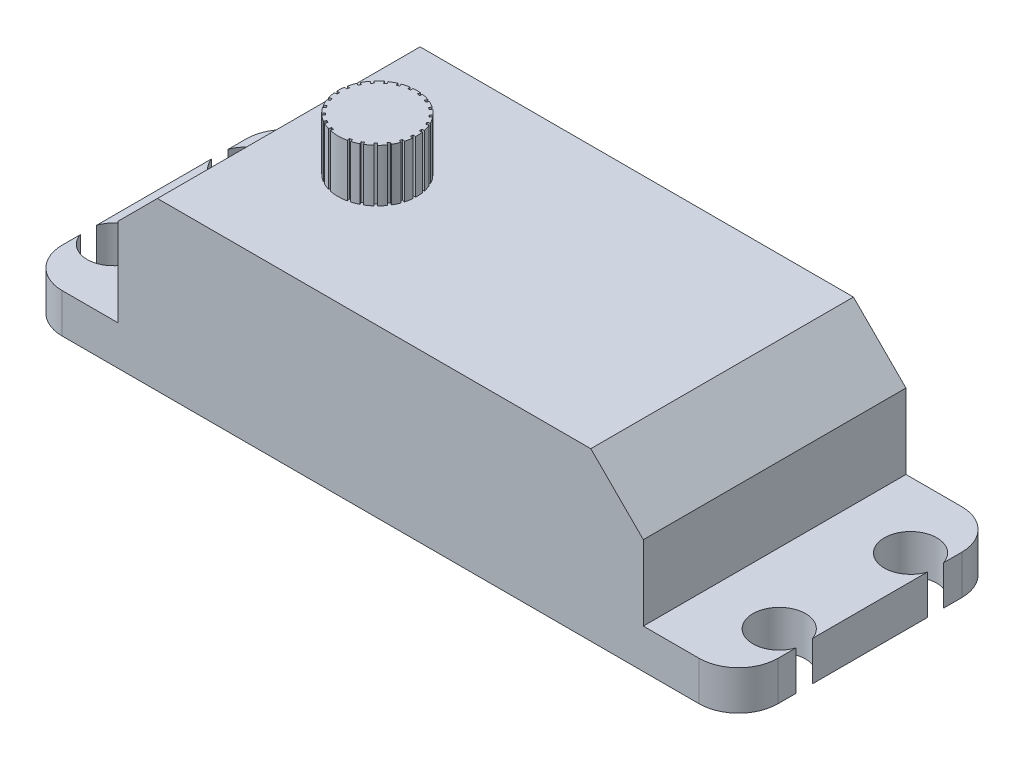
SolidWorks part; units mm, degrees
ref_plane "前视基准面" through (0, 0, 0) normal (0, 0, 1) x (1, 0, 0)
ref_plane "上视基准面" through (0, 0, 0) normal (0, 1, 0) x (1, 0, 0)
ref_plane "右视基准面" through (0, 0, 0) normal (1, 0, 0) x (0, 0, -1)
sketch "草图1" plane through (0, 0, 0) normal (0, 0, 1) x (1, 0, 0)
  line L1 (-20, 6.35) -> (20, 6.35)
  line L2 (-20, 6.35) -> (-20, -6.35)
  line L3 (-20, -6.35) -> (20, -6.35)
  line L4 (20, 6.35) -> (20, -6.35)
  line L5 (-20, 6.35) -> (20, -6.35) construction
  line L6 (-20, -6.35) -> (20, 6.35) construction
  point P0 (0, 0)
  dimension "D1" = 40
  dimension "D2" = 12.7
extrude "凸台-拉伸1" add sketch "草图1" along normal blind 20
sketch "草图3" plane through (0, -6.35, 0) normal (0, -1, 0) x (1, 0, 0)
  line L1 (-20, 20) -> (-24.25, 20)
  line L2 (-20, 20) -> (-20, 0)
  line L3 (-20, 0) -> (-24.25, 0)
  line L4 (-27.25, 17) -> (-27.25, 3)
  line L5 (20, 20) -> (24.25, 20)
  line L6 (20, 20) -> (20, 0)
  line L7 (20, 0) -> (24.25, 0)
  line L8 (27.25, 17) -> (27.25, 3)
  arc A0 (24.25, 0) -> (27.25, 3) centre (24.25, 3) ccw
  arc A1 (27.25, 17) -> (24.25, 20) centre (24.25, 17) ccw
  arc A2 (-24.25, 0) -> (-27.25, 3) centre (-24.25, 3) cw
  arc A3 (-27.25, 17) -> (-24.25, 20) centre (-24.25, 17) cw
  point P12 (27.25, 0)
  point P17 (-27.25, 0)
  dimension "D3" = 3
  dimension "D1" = 7.25
  dimension "D2" = 7.25
extrude "凸台-拉伸4" add sketch "草图3" against normal blind 3
sketch "草图4" plane through (0, -6.35, 0) normal (0, -1, 0) x (1, 0, 0)
  line L0 (-24.25, 20) -> (24.25, 20) construction
  line L1 (-24.25, 0) -> (24.25, 0) construction
  line L2 (-27.25, 17) -> (-27.25, 3) construction
  line L3 (27.25, 3) -> (27.25, 17) construction
  circle A0 centre (-25.35, 15) radius 2
  circle A1 centre (-25.35, 5) radius 2
  circle A2 centre (25.35, 15) radius 2
  circle A3 centre (25.35, 5) radius 2
  dimension "D1" = 4
  dimension "D2" = 4
  dimension "D3" = 4
  dimension "D4" = 4
  dimension "D5" = 10
  dimension "D6" = 10
  dimension "D7" = 0
  dimension "D8" = 5
  dimension "D9" = 5
  dimension "D10" = 5
  dimension "D11" = 1.9
  dimension "D12" = 1.9
extrude "切除-拉伸1" cut sketch "草图4" against normal blind 3
chamfer "倒角2" distance 4 angle 45 1 edges at (20, 6.35, 10)
chamfer "倒角3" distance 3 angle 45 1 edges at (-20, 6.35, 10)
sketch "草图5" plane through (0, 6.35, 0) normal (0, 1, 0) x (1, 0, 0)
  line L1 (-27.25, -14.3755) -> (-27.25, -5.6245) construction
  circle A0 centre (-10.25, -10) radius 3
  point P2 (0, 0)
  dimension "D1" = 6
  dimension "D2" = 17
extrude "凸台-拉伸5" add sketch "草图5" along normal blind 4
ref_plane "基准面1" through (0, 0, 13) normal (0, 0, 1) x (1, 0, 0)
sketch "草图6" plane through (0, 0, 13) normal (0, 0, 1) x (1, 0, 0)
  line L0 (-7.25, 10.35) -> (-13.25, 10.35) construction
  line L1 (-10.35, 10.35) -> (-10.15, 10.35)
  line L2 (-10.35, 10.35) -> (-10.35, 6.35)
  line L3 (-10.35, 6.35) -> (-10.15, 6.35)
  line L4 (-10.15, 10.35) -> (-10.15, 6.35)
  line L5 (16, 6.35) -> (-17, 6.35) construction
  dimension "D1" = 0.2
  dimension "D2" = 2.9
  dimension "D3" = 2.9
extrude "切除-拉伸2" cut sketch "草图6" against normal blind 0.2
pattern_circular "阵列(圆周)1" count 25 over 360 about axis through (-10.25, 10.35, 10) along (0, -1, 0) of "切除-拉伸2", "凸台-拉伸5"
